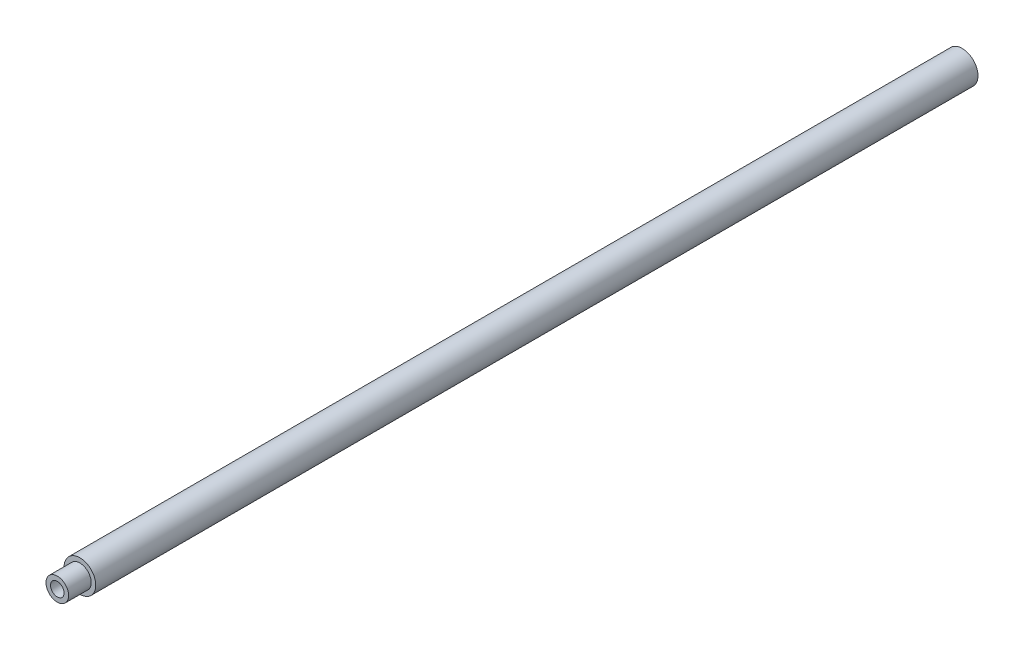
SolidWorks part; units mm, degrees
ref_plane "Front Plane" through (0, 0, 0) normal (0, 0, 1) x (1, 0, 0)
ref_plane "Top Plane" through (0, 0, 0) normal (0, 1, 0) x (1, 0, 0)
ref_plane "Right Plane" through (0, 0, 0) normal (1, 0, 0) x (0, 0, -1)
sketch "Sketch1" plane through (0, 0, 0) normal (0, 0, 1) x (1, 0, 0)
  circle A0 centre (0, 0) radius 3.5
  dimension "D1" = 7
extrude "Boss-Extrude1" add sketch "Sketch1" along normal blind 200
sketch "Sketch2" plane through (0, 0, 0) normal (0, 0, -1) x (-1, 0, 0)
  circle A0 centre (0, 0) radius 2
  dimension "D1" = 4
extrude "Cut-Extrude1" cut sketch "Sketch2" against normal blind 15
sketch "Sketch3" plane through (0, 0, 200) normal (0, 0, 1) x (1, 0, 0)
  circle A0 centre (0, 0) radius 3.5
  circle A1 centre (0, 0) radius 2.5
  dimension "D1" = 5
  dimension "D2" = 7
extrude "Cut-Extrude2" cut sketch "Sketch3" against normal blind 5
sketch "Sketch4" plane through (0, 0, 200) normal (0, 0, 1) x (1, 0, 0)
  circle A0 centre (0, 0) radius 1.5
  dimension "D1" = 3
extrude "Cut-Extrude3" cut sketch "Sketch4" against normal blind 20
